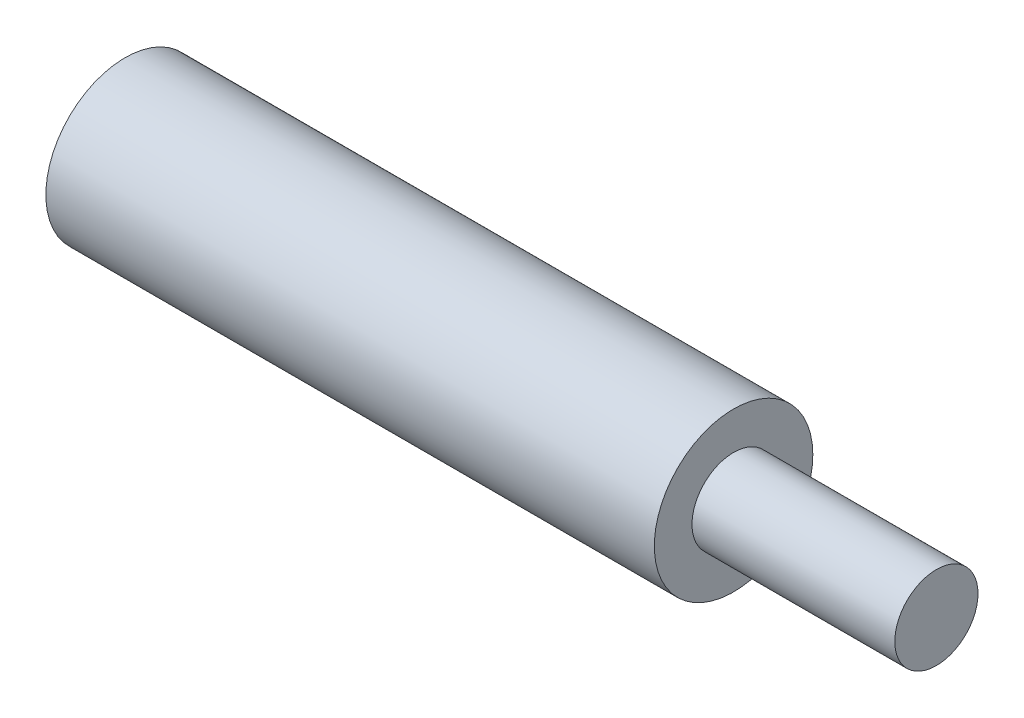
SolidWorks part; units mm, degrees
ref_plane "Front" through (0, 0, 0) normal (0, 0, 1) x (1, 0, 0)
ref_plane "Top" through (0, 0, 0) normal (0, 1, 0) x (1, 0, 0)
ref_plane "Right" through (0, 0, 0) normal (1, 0, 0) x (0, 0, -1)
sketch "Sketch1" plane through (0, 0, 0) normal (1, 0, 0) x (0, 0, -1)
  circle A0 centre (0, 0) radius 20
  dimension "D1" = 40
extrude "Boss-Extrude1" add sketch "Sketch1" along normal blind 390
sketch "Sketch2" plane through (0, 0, 0) normal (1, 0, 0) x (0, 0, -1)
  circle A0 centre (0, 0) radius 38.1
  dimension "D1" = 76.2
extrude "Boss-Extrude2" add sketch "Sketch2" along normal blind 292.5
